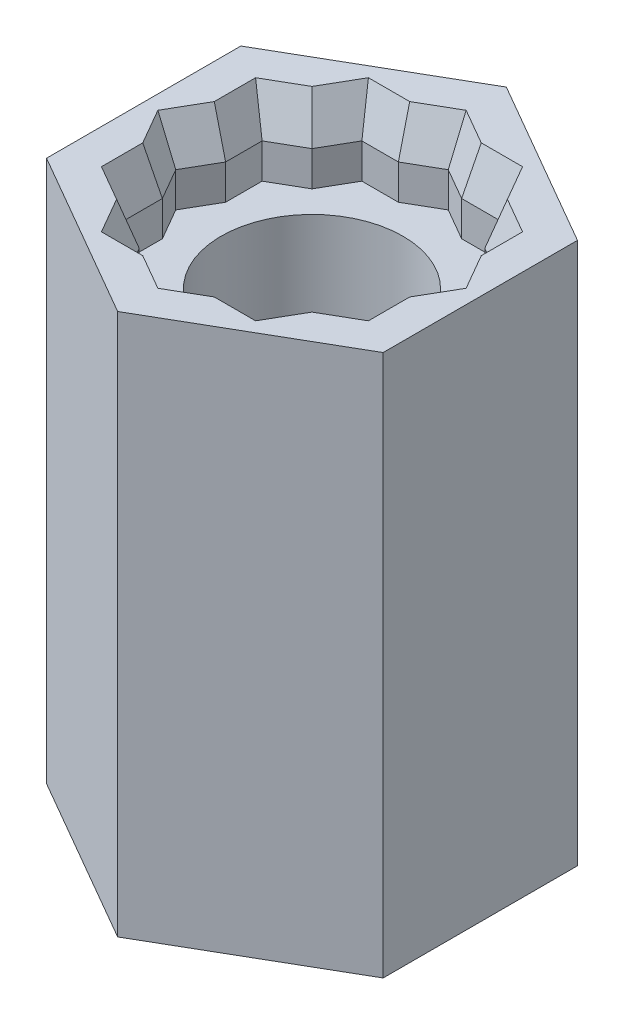
SolidWorks part; units mm, degrees
ref_plane "Front Plane" through (0, 0, 0) normal (0, 0, 1) x (1, 0, 0)
ref_plane "Top Plane" through (0, 0, 0) normal (0, 1, 0) x (1, 0, 0)
ref_plane "Right Plane" through (0, 0, 0) normal (1, 0, 0) x (0, 0, -1)
sketch "Sketch1" plane through (0, 0, 0) normal (0, 1, 0) x (1, 0, 0)
  line L1 (15.25, 8.8046) -> (0, 17.6092)
  line L2 (0, 17.6092) -> (-15.25, 8.8046)
  line L3 (-15.25, 8.8046) -> (-15.25, -8.8046)
  line L4 (-15.25, -8.8046) -> (0, -17.6092)
  line L5 (0, -17.6092) -> (15.25, -8.8046)
  line L6 (15.25, -8.8046) -> (15.25, 8.8046)
  line L7 (21.75, 12.5574) -> (0, 25.1147)
  line L8 (0, 25.1147) -> (-21.75, 12.5574)
  line L9 (-21.75, 12.5574) -> (-21.75, -12.5574)
  line L10 (-21.75, -12.5574) -> (0, -25.1147)
  line L11 (0, -25.1147) -> (21.75, -12.5574)
  line L12 (21.75, -12.5574) -> (21.75, 12.5574)
  circle A0 centre (0, 0) radius 15.25 construction
  circle A1 centre (0, 0) radius 21.75 construction
  dimension "D1" = 6.5
  dimension "D2" = 30.5
extrude "Boss-Extrude1" add sketch "Sketch1" along normal blind 10
sketch "Sketch2" plane through (0, 0, 0) normal (0, -1, 0) x (1, 0, 0)
  line L0 (-21.75, -12.5574) -> (-21.75, 12.5574) construction
  line L1 (21.75, 12.5574) -> (0, 25.1147)
  line L2 (0, 25.1147) -> (-21.75, 12.5574)
  line L3 (-21.75, 12.5574) -> (-21.75, -12.5574)
  line L4 (-21.75, -12.5574) -> (0, -25.1147)
  line L5 (0, -25.1147) -> (21.75, -12.5574)
  line L6 (21.75, -12.5574) -> (21.75, 12.5574)
  circle A0 centre (0, 0) radius 11.75
  circle A1 centre (0, 0) radius 21.75 construction
  dimension "D1" = 23.5
extrude "Boss-Extrude2" add sketch "Sketch2" along normal blind 40
sketch "Sketch3" plane through (0, -40, 0) normal (0, -1, 0) x (1, 0, 0)
  line L0 (-21.75, 12.5574) -> (-21.75, -12.5574) construction
  line L1 (21.75, 12.5574) -> (0, 25.1147)
  line L2 (0, 25.1147) -> (-21.75, 12.5574)
  line L3 (-21.75, 12.5574) -> (-21.75, -12.5574)
  line L4 (-21.75, -12.5574) -> (0, -25.1147)
  line L5 (0, -25.1147) -> (21.75, -12.5574)
  line L6 (21.75, -12.5574) -> (21.75, 12.5574)
  circle A0 centre (0, 0) radius 21.75 construction
extrude "Boss-Extrude3" add sketch "Sketch3" along normal blind 20
sketch "Sketch4" plane through (0, -60, 0) normal (0, -1, 0) x (1, 0, 0)
  line L0 (-2.6181, 1.66) -> (-2.6181, -1.66)
  line L1 (-2.4989, 1.66) -> (-2.4989, -1.66) construction
  arc A0 (-2.6181, -1.66) -> (-2.6181, 1.66) centre (0, 0) ccw
  circle A1 centre (0, 0) radius 3 construction
  dimension "D1" = 6.2
  dimension "D3" = 6
  dimension "D2" = 3.32
  dimension "D4" = 3.32
extrude "Cut-Extrude1" cut sketch "Sketch4" against normal blind 16
sketch "Sketch5" plane through (0, 10, 0) normal (0, 1, 0) x (1, 0, 0)
  line L0 (0, 0) -> (-10.875, 18.8361) construction
  line L1 (8.8046, 15.25) -> (-8.8046, 15.25)
  line L2 (-8.8046, 15.25) -> (-17.6092, 0)
  line L3 (-17.6092, 0) -> (-8.8046, -15.25)
  line L4 (-8.8046, -15.25) -> (8.8046, -15.25)
  line L5 (8.8046, -15.25) -> (17.6092, 0)
  line L6 (17.6092, 0) -> (8.8046, 15.25)
  line L7 (0, 25.1147) -> (-21.75, 12.5574) construction
  circle A0 centre (0, 0) radius 15.25 construction
  point P1 (0, 0)
  dimension "D1" = 30.5
extrude "Cut-Extrude2" cut sketch "Sketch5" against normal blind 10
chamfer "Chamfer1" distance 2 angle 70 24 edges at (-9.9842, 10, -13.2069) (-13.2069, 10, -9.9842) (-15.25, 10, -6.4454) (-16.4296, 10, -2.0431) (-16.4296, 10, 2.0431) (-15.25, 10, 6.4454) (-13.2069, 10, 9.9842) (-9.9842, 10, 13.2069) (-6.4454, 10, 15.25) (-2.0431, 10, 16.4296) (2.0431, 10, 16.4296) (6.4454, 10, 15.25) (9.9842, 10, 13.2069) (13.2069, 10, 9.9842) (15.25, 10, 6.4454) (16.4296, 10, 2.0431) (16.4296, 10, -2.0431) (15.25, 10, -6.4454) (13.2069, 10, -9.9842) (9.9842, 10, -13.2069) (6.4454, 10, -15.25) (2.0431, 10, -16.4296) (-2.0431, 10, -16.4296) (-6.4454, 10, -15.25)
